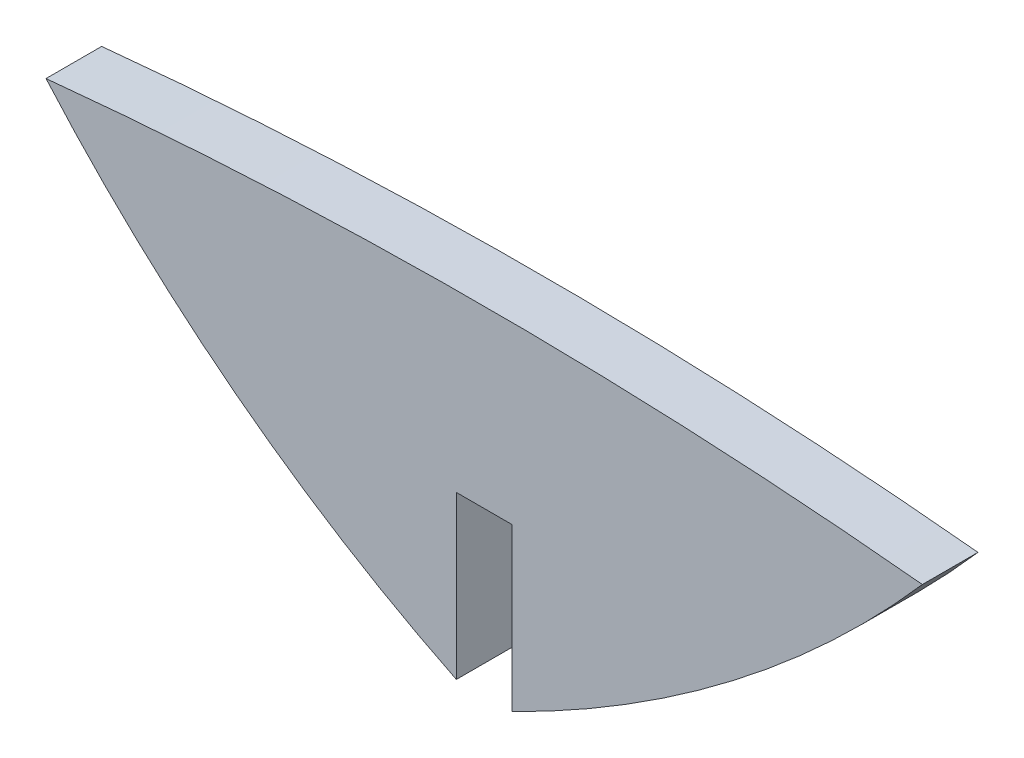
SolidWorks part; units mm, degrees
ref_plane "Front Plane" through (0, 0, 0) normal (0, 0, 1) x (1, 0, 0)
ref_plane "Top Plane" through (0, 0, 0) normal (0, 1, 0) x (1, 0, 0)
ref_plane "Right Plane" through (0, 0, 0) normal (1, 0, 0) x (0, 0, -1)
ref_plane "Plane1" through (0, 0, 1.5875) normal (0, 0, 1) x (1, 0, 0)
sketch "Sketch2" plane through (0, 0, 1.5875) normal (0, 0, 1) x (1, 0, 0)
  line L0 (-1.5875, 357.6599) -> (1.5875, 357.6599) construction
  line L1 (0, 325.0814) -> (0, 347.665) construction
  line L2 (-1.5875, 325.0814) -> (-1.5875, 347.665)
  line L3 (1.5875, 325.0814) -> (1.5875, 347.665)
  line L4 (-25, 356.4084) -> (25, 356.4084) construction
  line L5 (-1.5875, 347.665) -> (1.5875, 347.665)
  arc A2 (-25, 356.4084) -> (0, 337.665) centre (31.503, 405.7279) ccw
  arc A3 (0, 337.665) -> (25, 356.4084) centre (-31.503, 405.7279) ccw
  arc A4 (-1.5875, 325.0814) -> (1.5875, 325.0814) centre (0, 325.0814) ccw
  arc A5 (1.5875, 347.665) -> (-1.5875, 347.665) centre (0, 347.665) ccw
  arc A6 (25, 356.4084) -> (-25, 356.4084) centre (0, 107.34) ccw
  arc A7 (79.7117, 348.5081) -> (-79.7117, 348.5081) centre (0, 107.34) ccw construction
  point P10 (0, 357.6599)
  point P11 (0, 336.3732)
  point P14 (0, 356.4084)
  dimension "D2" = 75
  dimension "D1" = 10
  dimension "D3" = 50
extrude "Boss-Extrude1" add sketch "Sketch2" along normal mid plane 3.175
